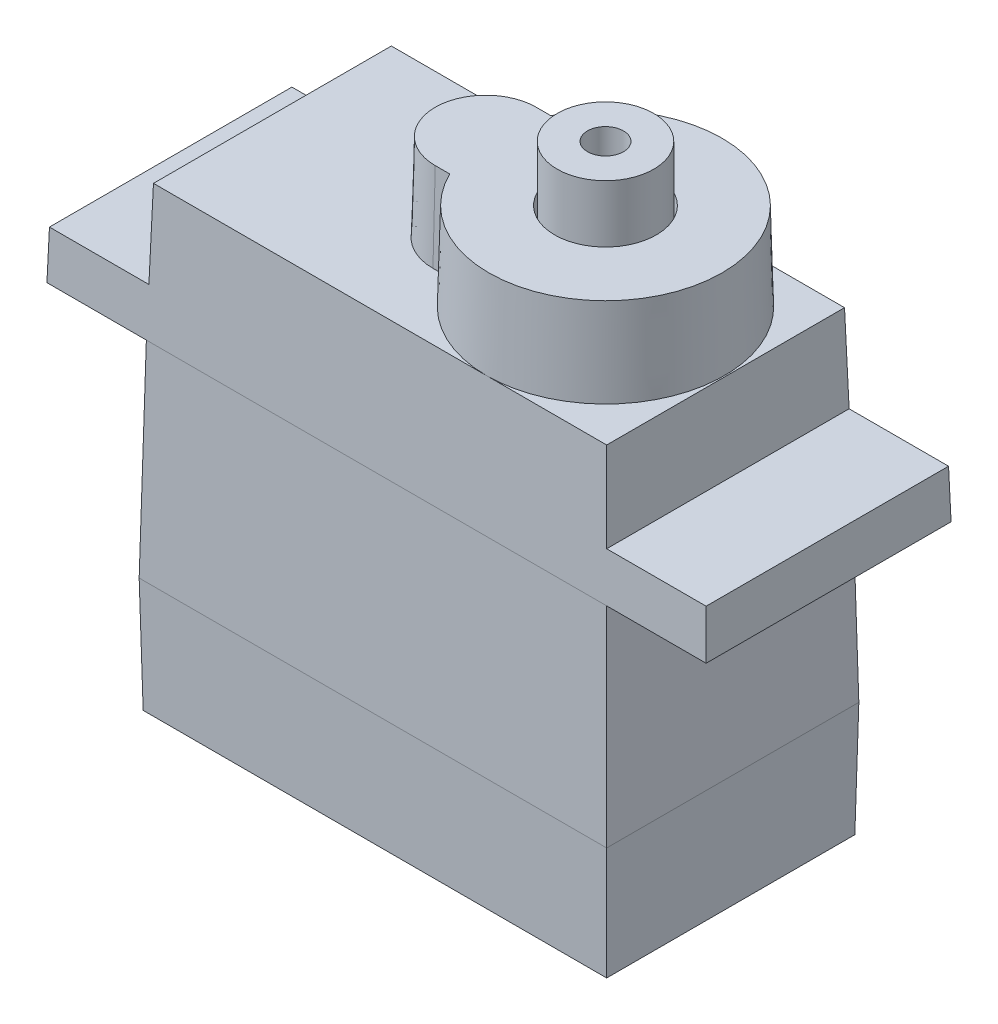
SolidWorks part; units mm, degrees
ref_plane "Front Plane" through (0, 0, 0) normal (0, 0, 1) x (1, 0, 0)
ref_plane "Top Plane" through (0, 0, 0) normal (0, 1, 0) x (1, 0, 0)
ref_plane "Right Plane" through (0, 0, 0) normal (1, 0, 0) x (0, 0, -1)
sketch "Sketch8" plane through (0, 0, 0) normal (0, 1, 0) x (1, 0, 0)
  line L1 (16.25, -6.0388) -> (-16.25, -6.0389)
  line L2 (16.25, -6.0388) -> (16.25, 6.0389)
  line L3 (16.25, 6.0389) -> (-16.25, 6.0388)
  line L4 (-16.25, -6.0389) -> (-16.25, 6.0388)
  line L5 (16.25, -6.0388) -> (-16.25, 6.0388) construction
  line L6 (16.25, 6.0389) -> (-16.25, -6.0389) construction
  point P0 (0, 0)
  dimension "D1" = 32.5
  dimension "D2" = 12.0777
extrude "Body Mounting Plate" add sketch "Sketch8" along normal blind 2.3749 separate body
sketch "Sketch9" plane through (0, 2.3749, 0) normal (0, 1, 0) x (1, 0, 0)
  line L0 (16.25, 6.0389) -> (-16.25, 6.0388) construction
  line L1 (11.3474, -6.0388) -> (-11.3474, -6.0388)
  line L2 (11.3474, -6.0388) -> (11.3474, 6.0388)
  line L3 (11.3474, 6.0388) -> (-11.3474, 6.0388)
  line L4 (-11.3474, -6.0388) -> (-11.3474, 6.0388)
  line L5 (11.3474, -6.0388) -> (-11.3474, 6.0388) construction
  line L6 (11.3474, 6.0388) -> (-11.3474, -6.0388) construction
  line L7 (0, 6.0388) -> (0, -6.0389) construction
  line L8 (-16.25, -6.0389) -> (16.25, -6.0388) construction
  point P0 (0, 0)
  dimension "D1" = 22.6949
extrude "Body Top" add sketch "Sketch9" along normal blind 4.318
draft "Body Top Draft 1.5" type of draft neutral plane draft angle 1.5 faces to draft 6 face at (11.3474, 5.6134, 1.5097) face at (16.25, 1.1875, 0) face at (0.6128, 3.4004, -6.0388) face at (-11.3474, 5.6134, -1.5097) face at (-16.25, 1.1875, 0) face at (-0.6128, 3.4004, 6.0388) neutral plane through (0, 0, 0) neutral plane normal (0, -1, 0) reverse direction yes parameters "D1"=1.5
sketch "Sketch10" plane through (0, 0, 0) normal (0, -1, 0) x (1, 0, 0)
  line L4 (11.3474, 6.0388) -> (-11.3474, 6.0388)
  line L5 (-11.3474, 6.0388) -> (-11.3474, -6.0388)
  line L6 (-11.3474, -6.0388) -> (11.3474, -6.0388)
  line L7 (11.3474, -6.0388) -> (11.3474, 6.0388)
  line L8 (11.3474, 6.0388) -> (-11.3474, 6.0388)
  line L9 (-11.3474, 6.0388) -> (-11.3474, -6.0388)
  line L10 (-11.3474, -6.0388) -> (11.3474, -6.0388)
  line L11 (11.3474, -6.0388) -> (11.3474, 6.0388)
  dimension "D1" = 0
extrude "Body Middle" add sketch "Sketch10" along normal blind 10.16 draft 1 draft outward yes
sketch "Sketch11" plane through (0, -10.16, 0) normal (0, -1, 0) x (1, 0, 0)
  line L4 (11.5248, -6.2162) -> (11.5248, 6.2162)
  line L5 (11.5248, 6.2162) -> (-11.5248, 6.2162)
  line L6 (-11.5248, 6.2162) -> (-11.5248, -6.2162)
  line L7 (-11.5248, -6.2162) -> (11.5248, -6.2162)
  line L8 (11.5248, -6.2162) -> (11.5248, 6.2162)
  line L9 (11.5248, 6.2162) -> (-11.5248, 6.2162)
  line L10 (-11.5248, 6.2162) -> (-11.5248, -6.2162)
  line L11 (-11.5248, -6.2162) -> (11.5248, -6.2162)
  dimension "D1" = 0
extrude "Body Bodom" add sketch "Sketch11" along normal offset from surface 22.5044 draft 1
sketch "Sketch12" plane through (0, 6.6929, 0) normal (0, 1, 0) x (1, 0, 0)
  line L0 (-11.1722, 0) -> (11.1722, 0) construction
  line L1 (-11.1722, 5.8636) -> (-11.1722, -5.8636) construction
  line L2 (11.1722, -5.8636) -> (11.1722, 5.8636) construction
  line L5 (-0.653, 2.6035) -> (-0.0039, 2.6035)
  line L6 (-0.653, -2.6035) -> (-0.0039, -2.6035)
  line L7 (11.1722, 5.8636) -> (-11.1722, 5.8636) construction
  line L9 (16.25, -6.0388) -> (16.25, 6.0389) construction
  arc A0 (-0.0039, -2.6035) -> (-0.0039, 2.6035) centre (5.25, 0) ccw
  arc A2 (-0.653, 2.6035) -> (-0.653, -2.6035) centre (-0.653, 0) ccw
  dimension "D1" = 5.903
  dimension "D2" = 2.6035
  dimension "D3" = 11
extrude "Body Topper" add sketch "Sketch12" along normal offset from surface 26.8351 draft 1.5
sketch "Sketch13" plane through (0, 11.0236, 0) normal (0, 1, 0) x (1, 0, 0)
  line L0 (11.1722, -5.8636) -> (11.1722, 5.8636) construction
  circle A0 centre (5.25, 0) radius 2.3812
  arc A1 (-0.653, 2.4901) -> (-0.653, -2.4901) centre (-0.653, 0) ccw construction
  point P5 (11.1722, 0)
  point P8 (-3.1431, 0)
  dimension "D1" = 4.7625
  dimension "D2" = 11.8251
extrude "Spindle" add sketch "Sketch13" along normal offset from surface (2.7432 mm away) 29.5783 up to face at (0, -15.8115, 0)
sketch "Sketch18" plane through (0, 11.0236, 0) normal (0, 1, 0) x (1, 0, 0)
  circle A0 centre (5.25, 0) radius 2.3812 construction
  circle A1 centre (5.25, 0) radius 2.3812
  circle A2 centre (5.25, 0) radius 2.5082
  dimension "D1" = 0.127
extrude "Spindle Opening" cut sketch "Sketch18" against normal blind 3.175
sketch "Sketch14" plane through (0, 13.7668, 0) normal (0, 1, 0) x (1, 0, 0)
  line L0 (11.1722, -5.8636) -> (11.1722, 5.8636) construction
  line L1 (-16.25, 6.0388) -> (-16.25, -6.0389) construction
  circle A0 centre (5.25, 0) radius 0.889
  dimension "D1" = 1.778
extrude "Spindle Screw Hole" cut sketch "Sketch14" against normal blind 6.35
